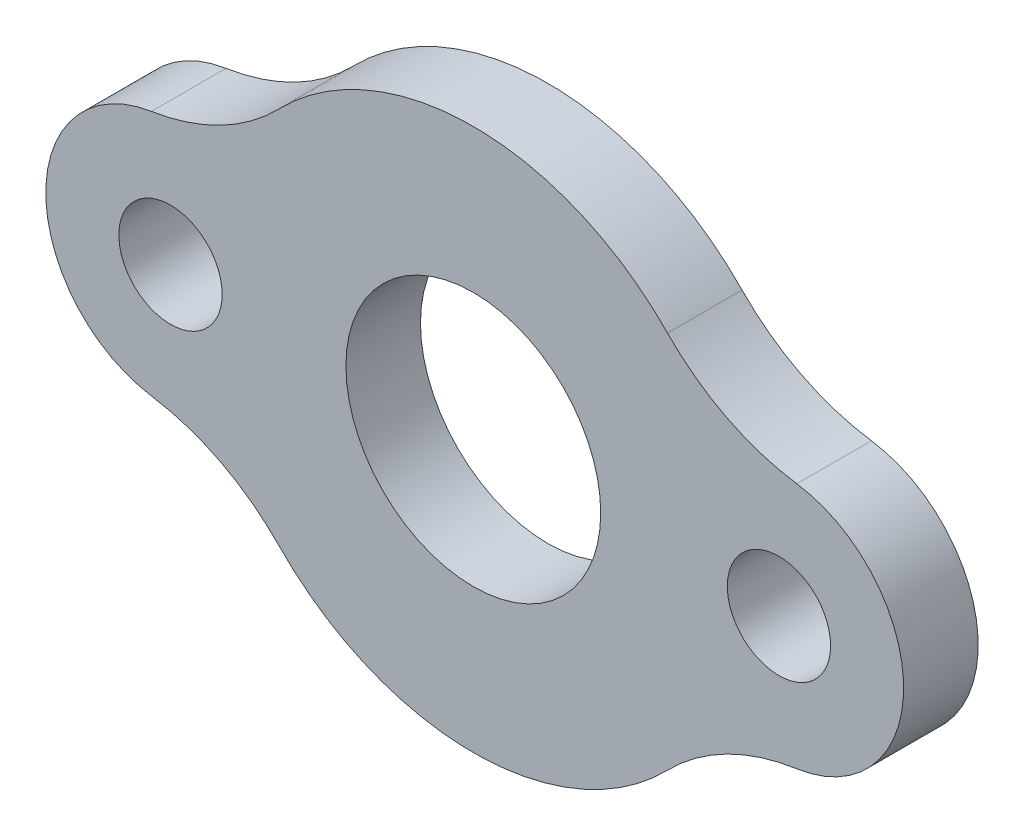
SolidWorks part; units mm, degrees
ref_plane "Plano frontal" through (0, 0, 0) normal (0, 0, 1) x (1, 0, 0)
ref_plane "Plano superior" through (0, 0, 0) normal (0, 1, 0) x (1, 0, 0)
ref_plane "Plano direito" through (0, 0, 0) normal (1, 0, 0) x (0, 0, -1)
sketch "Esboço1" plane through (0, 0, 0) normal (0, 0, 1) x (1, 0, 0)
  arc A0 (-4.3021, -4.1823) -> (-3.8426, -4.6081) centre (0, 0) ccw
  arc A1 (-3.8426, -4.6081) -> (3.8426, -4.6081) centre (0, 0) ccw
  arc A2 (3.8426, -4.6081) -> (4.2963, -4.1883) centre (0, 0) ccw
  arc A3 (3.849, 4.6028) -> (-3.8362, 4.6134) centre (0, 0) ccw
  arc A4 (-3.8362, 4.6134) -> (-4.3021, 4.1823) centre (0, 0) ccw
  arc A5 (4.2963, 4.1883) -> (3.849, 4.6028) centre (0, 0) ccw
  arc A6 (-7.1222, 2.7265) -> (-7.1222, -2.7265) centre (-6.7, 0) ccw
  arc A7 (7.1583, -2.7303) -> (7.1583, 2.7303) centre (6.762, 0) ccw
  arc A8 (-4.3021, -4.1823) -> (-7.1222, -2.7265) centre (-7.8872, -7.6676) ccw
  arc A9 (7.1583, -2.7303) -> (4.2963, -4.1883) centre (7.8766, -7.6785) ccw
  arc A10 (4.2963, 4.1883) -> (7.1583, 2.7303) centre (7.8766, 7.6785) ccw
  arc A11 (-7.1222, 2.7265) -> (-4.3021, 4.1823) centre (-7.8872, 7.6676) ccw
  circle A12 centre (6.762, 0) radius 1.143
  circle A13 centre (-6.7, 0) radius 1.143
  circle A15 centre (0, 0) radius 2.8192
extrude "Ressalto-extrusão1" add sketch "Esboço1" along normal blind 1.65
